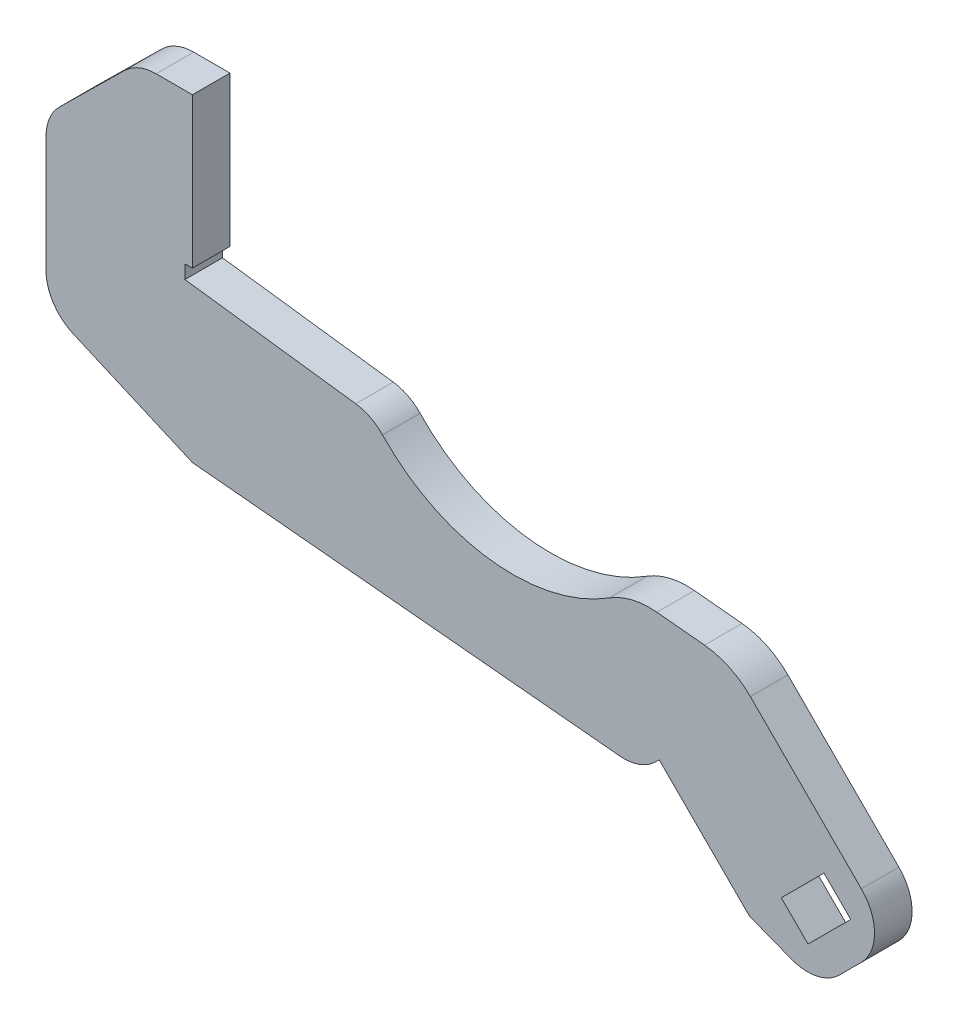
SolidWorks part; units mm, degrees
material "PBT General Purpose"
ref_plane "Front Plane" through (0, 0, 0) normal (0, 0, 1) x (1, 0, 0)
ref_plane "Top Plane" through (0, 0, 0) normal (0, 1, 0) x (1, 0, 0)
ref_plane "Right Plane" through (0, 0, 0) normal (1, 0, 0) x (0, 0, -1)
sketch "frame_outline" plane through (0, 0, 0) normal (0, 0, 1) x (1, 0, 0)
  line L0 (0, 0) -> (0, -0.6) construction
  line L1 (0, 0) -> (0.3, 0) construction
  line L2 (0, -0.6) -> (-0.05, -0.6) construction
  line L3 (0, 0) -> (4.9667, -4.9667) construction
  line L63 (-0.05, -0.6) -> (-0.05, -1.6)
  line L64 (-0.05, -0.6) -> (-0.4144, -0.6)
  line L65 (-0.4144, -0.6) -> (-1.025, -1.2016)
  line L66 (-1.025, -1.2016) -> (-1.025, -2.2972)
  line L67 (-1.025, -2.2972) -> (-0.05, -2.7212)
  line L71 (-0.05, -2.7212) -> (2.9356, -3.0041)
  line L72 (2.9356, -3.0041) -> (3.0582, -2.8815)
  line L73 (3.0582, -2.8815) -> (3.6593, -3.4825)
  line L74 (3.6593, -3.4825) -> (4.1203, -3.6607)
  line L75 (4.1203, -3.6607) -> (4.6167, -3.1643)
  line L76 (4.6167, -3.1643) -> (3.5388, -2.0864)
  line L77 (3.5388, -2.0864) -> (2.8549, -2.0196)
  line L78 (-0.1, -1.6906) -> (-0.1, -1.6)
  line L79 (-0.1, -1.6) -> (-0.05, -1.6)
  line L80 (3.8714, -3.2704) -> (4.0496, -3.4486)
  line L81 (3.8714, -3.2704) -> (4.1557, -2.9861)
  line L82 (4.0496, -3.4486) -> (4.3339, -3.1643)
  line L83 (4.1557, -2.9861) -> (4.3339, -3.1643)
  line L84 (0, -0.6) -> (0, -4.6335) construction
  line L85 (3.6593, -3.4825) -> (3.8714, -3.2704) construction
  line L86 (1.1495, -1.8531) -> (-0.1, -1.6906)
  arc A0 (1.1495, -1.8531) -> (2.8549, -2.0196) centre (2.0839, -1.1001) ccw
  point P25 (0, -2.3724)
  dimension "D2" = 0.3
  dimension "D3" = 0.6
  dimension "D8" = 1
  dimension "D4" = 45
  dimension "D1" = 0.05
  dimension "D5" = 0.125
  dimension "D7" = 0.05
  dimension "D10" = 0.85
  dimension "D11" = 0.252
  dimension "D12" = 0.402
  dimension "D13" = 0.3
  dimension "D14" = 0.2
  dimension "D15" = 0.2
  dimension "D16" = 0.1
  dimension "D17" = 4.2
extrude "Boss-Extrude1" add sketch "frame_outline" along normal mid plane 0.25
fillet "Fillet1" radius 0.3 7 edges at (4.6167, -3.1643, 0) (4.1203, -3.6607, 0) (1.1495, -1.8531, 0) (-0.4144, -0.6, 0) (-1.025, -1.2016, 0) (-1.025, -2.2972, 0) (2.9356, -3.0041, 0)
fillet "Fillet2" radius 0.5 2 edges at (3.5388, -2.0864, 0) (2.8549, -2.0196, 0)
equation "\"t\"= 0.25'thickness of the sheets"
equation "\"t_cf\" = 0.115'thickness of single carbon fiber layer"
equation "\"t_kapton\" = 0.025'thickness of single Kapton flex layer"
equation "\"t_fr4\" = 0.1'thickness of FR4 with copper layer"
equation "\"joint_flex\"= 0.1'Width of flextures gap"
equation "\"joint_flex_eff\"= 0.02'Width of flecture after castelation"
equation "\"joint_fold\"= 0.2'Width of folding joints for 90deg fold"
equation "\"gap_tolerance\"= 0.002'Width to have interfecence fit between carbon fiber inserts"
equation "\"assemble_angle\"= 90'Angle of assembly parts"
equation "\"D1@Boss-Extrude1\"=\"t\""
equation "\"link_lift\"= 0.5'Actuation linkage amplification for the lift motion"
equation "\"link_swing\"= 0.45'Actuation linkage amplification for the swing motion"
equation "\"D1@frame_outline\"=\"joint_flex\"/2"
equation "\"D5@frame_outline\"=\"t\"/2"
equation "\"D11@frame_outline\"=\"t\"+\"gap_tolerance\""
equation "\"D12@frame_outline\"=0.4+\"gap_tolerance\""
equation "\"D10@frame_outline\"=0.80mm+0.05"
